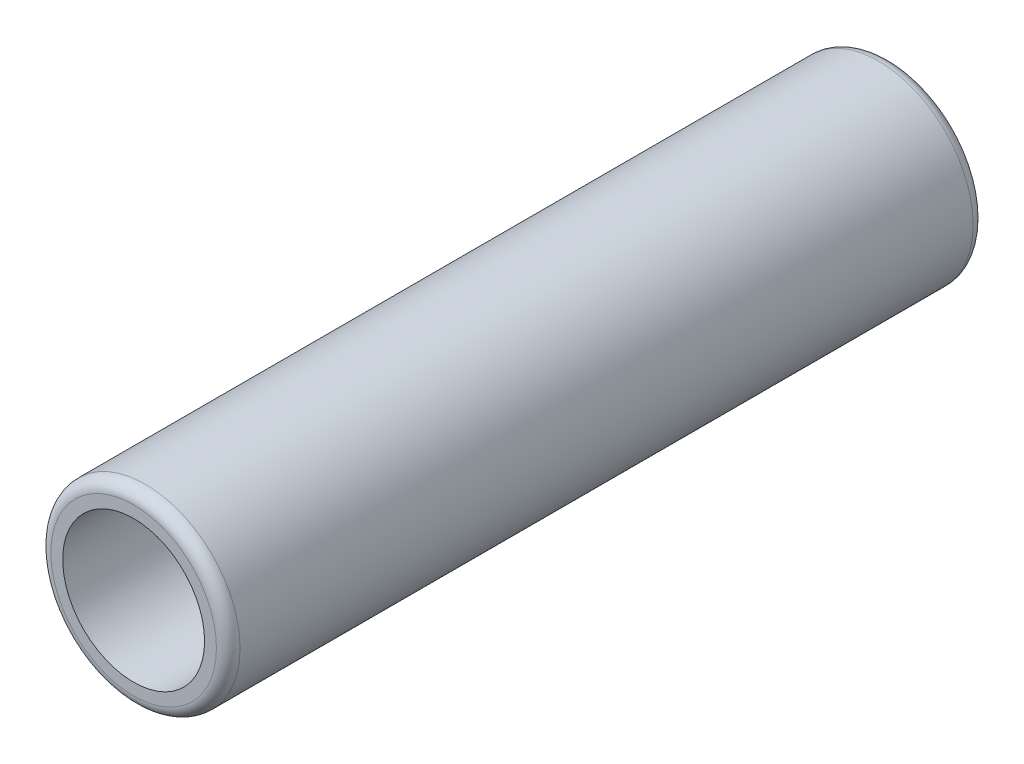
SolidWorks part; units mm, degrees
material "Простая углеродистая сталь"
ref_plane "Спереди" through (0, 0, 0) normal (0, 0, 1) x (1, 0, 0)
ref_plane "Сверху" through (0, 0, 0) normal (0, 1, 0) x (1, 0, 0)
ref_plane "Справа" through (0, 0, 0) normal (1, 0, 0) x (0, 0, -1)
sketch "Эскиз1" plane through (0, 0, 0) normal (0, 0, 1) x (1, 0, 0)
  circle A0 centre (0, 0) radius 4
  circle A1 centre (0, 0) radius 3
  dimension "D1" = 6
  dimension "D2" = 8
extrude "Бобышка-Вытянуть1" add sketch "Эскиз1" along normal blind 32
cosmetic thread "Условное изображение резьбы1" parameters "D2"=18
fillet "Скругление1" radius 0.5 2 edges at (4, 0, 0) (4, 0, 32)
